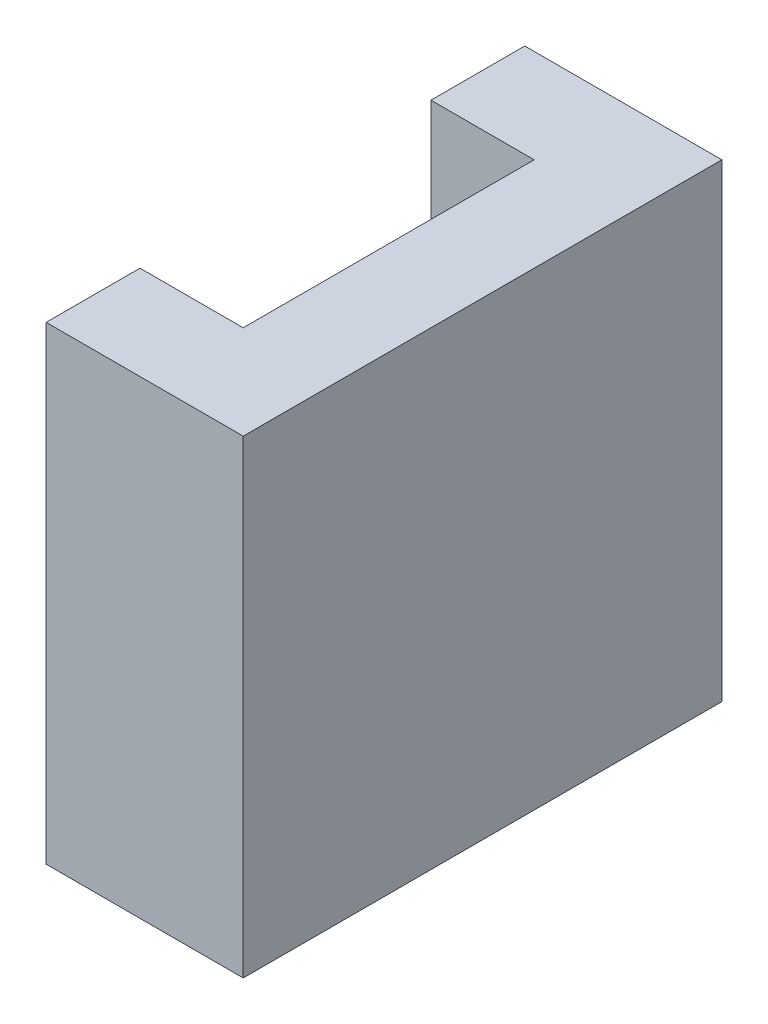
SolidWorks part; units mm, degrees
ref_plane "Front Plane" through (0, 0, 0) normal (0, 0, 1) x (1, 0, 0)
ref_plane "Top Plane" through (0, 0, 0) normal (0, 1, 0) x (1, 0, 0)
ref_plane "Right Plane" through (0, 0, 0) normal (1, 0, 0) x (0, 0, -1)
sketch "Sketch1" plane through (0, 0, 0) normal (1, 0, 0) x (0, 0, -1)
  line L1 (-14.8454, 13.1413) -> (0.6546, 13.1413)
  line L2 (-14.8454, 13.1413) -> (-14.8454, -6.8587)
  line L3 (-14.8454, -6.8587) -> (0.6546, -6.8587)
  line L4 (0.6546, 13.1413) -> (0.6546, -6.8587)
  line L5 (-19.8454, 13.1413) -> (5.6546, 13.1413)
  line L6 (-19.8454, 13.1413) -> (-19.8454, -11.8587)
  line L7 (-19.8454, -11.8587) -> (5.6546, -11.8587)
  line L8 (5.6546, 13.1413) -> (5.6546, -11.8587)
  dimension "D1" = 20
  dimension "D2" = 15.5
  dimension "D3" = 5
  dimension "D4" = 5
  dimension "D5" = 5
extrude "Boss-Extrude1" add sketch "Sketch1" along normal blind 5.5 contours L8 L5 L4 L3 L2 L6 L7
sketch "Sketch2" plane through (5.5, 0, 0) normal (1, 0, 0) x (0, 0, -1)
  line L6 (-19.8454, 13.1413) -> (5.6546, 13.1413)
  line L7 (-19.8454, 13.1413) -> (-19.8454, -11.8587)
  line L8 (-19.8454, -11.8587) -> (5.6546, -11.8587)
  line L9 (5.6546, 13.1413) -> (5.6546, -11.8587)
extrude "Boss-Extrude2" add sketch "Sketch2" along normal blind 5
